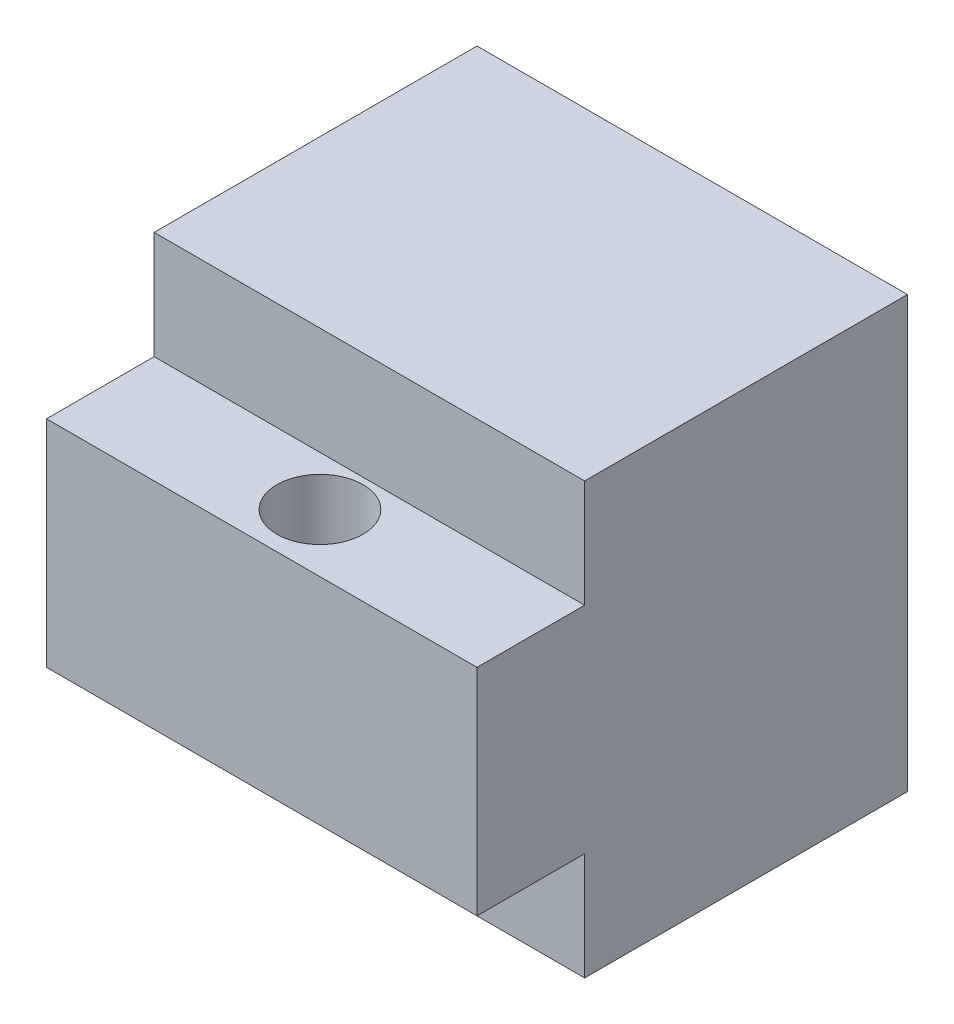
SolidWorks part; units mm, degrees
ref_plane "Front Plane" through (0, 0, 0) normal (0, 0, 1) x (1, 0, 0)
ref_plane "Top Plane" through (0, 0, 0) normal (0, 1, 0) x (1, 0, 0)
ref_plane "Right Plane" through (0, 0, 0) normal (1, 0, 0) x (0, 0, -1)
sketch "Sketch1" plane through (0, 0, 0) normal (1, 0, 0) x (0, 0, -1)
  line L0 (-2.5, 5) -> (5, 5)
  line L1 (-2.5, 5) -> (-2.5, 2.5)
  line L2 (-2.5, -5) -> (5, -5)
  line L3 (5, 5) -> (5, -5)
  line L4 (-2.5, 5) -> (5, -5) construction
  line L5 (-2.5, -5) -> (5, 5) construction
  line L6 (-2.5, -2.5) -> (-2.5, -5)
  line L7 (-5, 2.5) -> (-2.5, 2.5)
  line L8 (-5, 2.5) -> (-5, -2.5)
  line L9 (-5, -2.5) -> (-2.5, -2.5)
  line L10 (-5, 2.5) -> (-2.5, -2.5) construction
  line L11 (-5, -2.5) -> (-2.5, 2.5) construction
  point P4 (1.25, 0)
  point P6 (5, 0)
  point P10 (-3.75, 0)
  point P11 (-2.5, 0)
  point P12 (0, 0)
extrude "Boss-Extrude1" add sketch "Sketch1" along normal blind 10
sketch "Sketch3" plane through (0, 2.5, 0) normal (0, 1, 0) x (1, 0, 0)
  line L0 (5, -2.2958) -> (5, -5) construction
  line L1 (10, -5) -> (0, -5) construction
  circle A0 centre (5, -3.6479) radius 1
  point P4 (4.6297, -3.5635)
  point P5 (5, -5)
  point P8 (0, 0)
extrude "Cut-Extrude2" cut sketch "Sketch3" against normal through all
